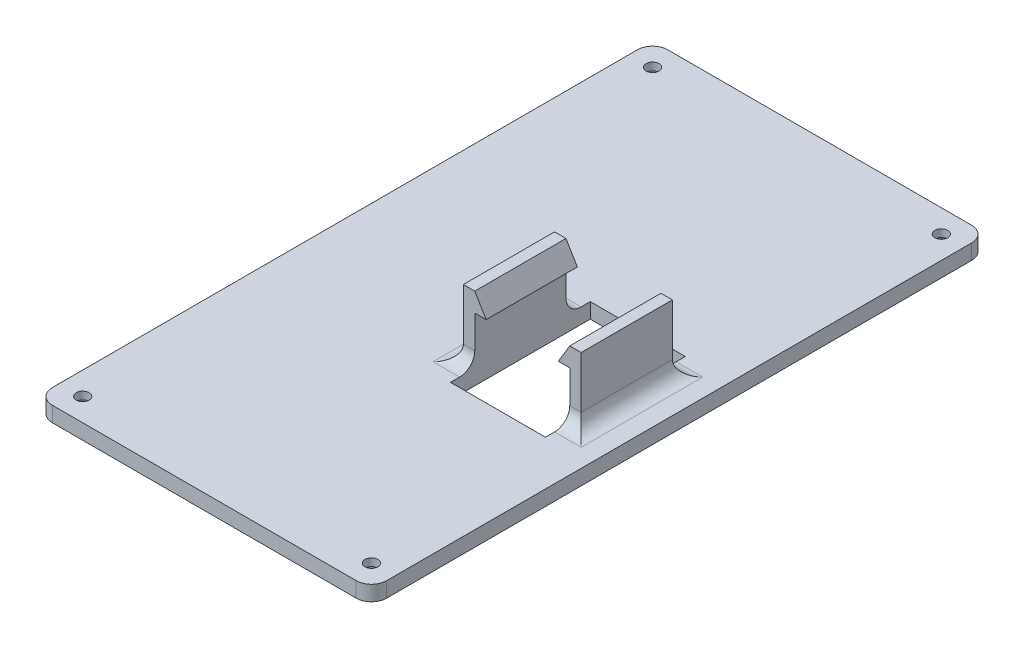
SolidWorks part; units mm, degrees
ref_plane "前视基准面" through (0, 0, 0) normal (0, 0, 1) x (1, 0, 0)
ref_plane "上视基准面" through (0, 0, 0) normal (0, 1, 0) x (1, 0, 0)
ref_plane "右视基准面" through (0, 0, 0) normal (1, 0, 0) x (0, 0, -1)
sketch "草图1" plane through (0, 0, 0) normal (0, 1, 0) x (1, 0, 0)
  line L1 (-22, 43) -> (22, 43)
  line L2 (-22, 43) -> (-22, -38)
  line L3 (-22, -38) -> (22, -38)
  line L4 (22, 43) -> (22, -38)
  dimension "D1" = 44
  dimension "D2" = 81
  dimension "D3" = 22
  dimension "D4" = 43
extrude "凸台-拉伸1" add sketch "草图1" along normal blind 2
sketch "草图12" plane through (0, 0, 0) normal (0, -1, 0) x (1, 0, 0)
  line L1 (3.5998, 9.2) -> (16.0998, 9.2)
  line L2 (3.5998, 9.2) -> (3.5998, -9.2)
  line L3 (3.5998, -9.2) -> (16.0998, -9.2)
  line L4 (16.0998, 9.2) -> (16.0998, -9.2)
  dimension "D1" = 18.4
  dimension "D2" = 9.2
  dimension "D3" = 12.5
extrude "切除-拉伸3" cut sketch "草图12" against normal blind 7.5
sketch "草图15" plane through (0, 2, 0) normal (0, 1, 0) x (1, 0, 0)
  line L0 (3.5998, 9.2) -> (3.5998, -9.2) construction
  line L1 (3.5998, 6) -> (2.0998, 6)
  line L2 (3.5998, 6) -> (3.5998, -6)
  line L3 (3.5998, -6) -> (2.0998, -6)
  line L4 (2.0998, 6) -> (2.0998, -6)
  line L5 (9.8498, 9.2) -> (9.8498, -16.7333) construction
  line L6 (16.0998, 9.2) -> (3.5998, 9.2) construction
  line L7 (17.5998, 6) -> (17.5998, -6)
  line L8 (16.0998, -6) -> (17.5998, -6)
  line L9 (16.0998, 6) -> (16.0998, -6)
  line L10 (16.0998, 6) -> (17.5998, 6)
  dimension "D1" = 1.5
  dimension "D2" = 12
  dimension "D3" = 6
extrude "凸台-拉伸10" add sketch "草图15" along normal blind 8.8
sketch "草图16" plane through (0, 0, 6) normal (0, 0, 1) x (1, 0, 0)
  line L0 (3.5998, 10.8) -> (5.0998, 8.3)
  line L1 (5.0998, 8.3) -> (3.5998, 8.3)
  line L2 (3.5998, 10.8) -> (3.5998, 2) construction
  line L3 (3.5998, 8.3) -> (3.5998, 10.8)
  dimension "D1" = 2.5
  dimension "D2" = 1.5
extrude "凸台-拉伸11" add sketch "草图16" against normal blind 12
sketch "草图18" plane through (0, 0, 6) normal (0, 0, 1) x (1, 0, 0)
  line L0 (16.0998, 10.8) -> (14.5998, 8.3)
  line L1 (14.5998, 8.3) -> (16.0998, 8.3)
  line L2 (16.0998, 10.8) -> (16.0998, 2) construction
  line L3 (16.0998, 8.3) -> (16.0998, 10.8)
  dimension "D1" = 2.5
  dimension "D2" = 1.5
extrude "凸台-拉伸12" add sketch "草图18" against normal blind 12
fillet "圆角2" radius 2 6 edges at (16.8498, 2, -6) (17.5998, 2, 0) (16.8498, 2, 6) (2.8498, 2, -6) (2.8498, 2, 6) (2.0998, 2, 0)
fillet "圆角3" radius 2 4 edges at (22, 1, 38) (-22, 1, 38) (-22, 1, -43) (22, 1, -43)
sketch "草图19" plane through (0, 2, 0) normal (0, 1, 0) x (1, 0, 0)
  line L0 (20, 43) -> (-20, 43) construction
  line L1 (-22, 41) -> (-22, -36) construction
  line L2 (0, 45.4667) -> (0, 30.1792) construction
  line L3 (-25.8822, 2.5) -> (-14.5047, 2.5) construction
  circle A0 centre (-19, 40) radius 0.85
  circle A1 centre (19, 40) radius 0.85
  circle A2 centre (19, -35) radius 0.85
  circle A3 centre (-19, -35) radius 0.85
  dimension "D3" = 1.7
  dimension "D1" = 3
  dimension "D2" = 3
extrude "切除-拉伸4" cut sketch "草图19" against normal blind 12
sketch "草图20" plane through (0, 0, 0) normal (0, -1, 0) x (1, 0, 0)
  circle A0 centre (-19, 35) radius 2
  circle A1 centre (19, 35) radius 2
  circle A2 centre (-19, -40) radius 2
  circle A3 centre (19, -40) radius 2
extrude "切除-拉伸5" cut sketch "草图20" against normal blind 1
equation "\"8。8\"=7.5"
